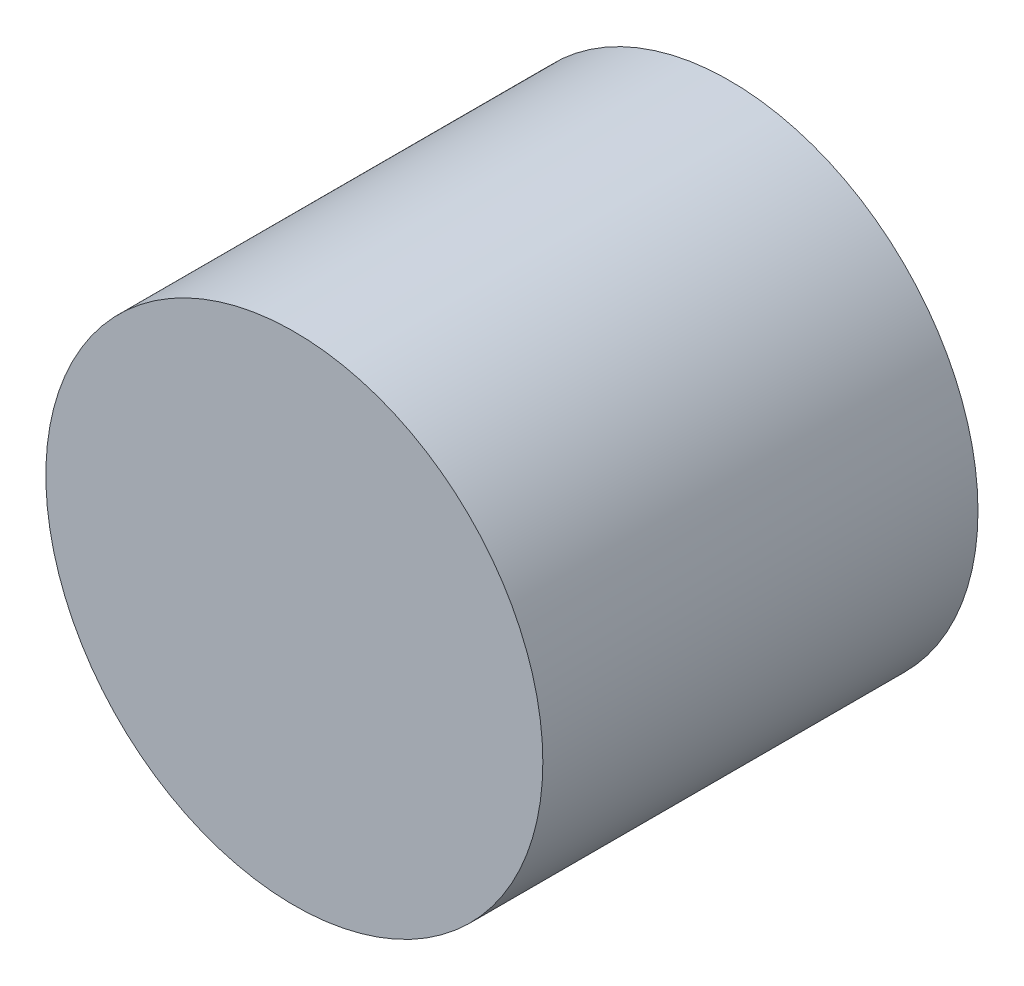
SolidWorks part; units mm, degrees
other "DetailItem1"
material "EN36A"
ref_plane "Front Plane" through (0, 0, 0) normal (0, 0, 1) x (1, 0, 0)
ref_plane "Top Plane" through (0, 0, 0) normal (0, 1, 0) x (1, 0, 0)
ref_plane "Right Plane" through (0, 0, 0) normal (1, 0, 0) x (0, 0, -1)
sketch "Sketch1" plane through (0, 0, 0) normal (0, 0, 1) x (1, 0, 0)
  circle A0 centre (0, 0) radius 7.995
  dimension "D1" = 15.99
extrude "Extrude1" add sketch "Sketch1" along normal blind 14
